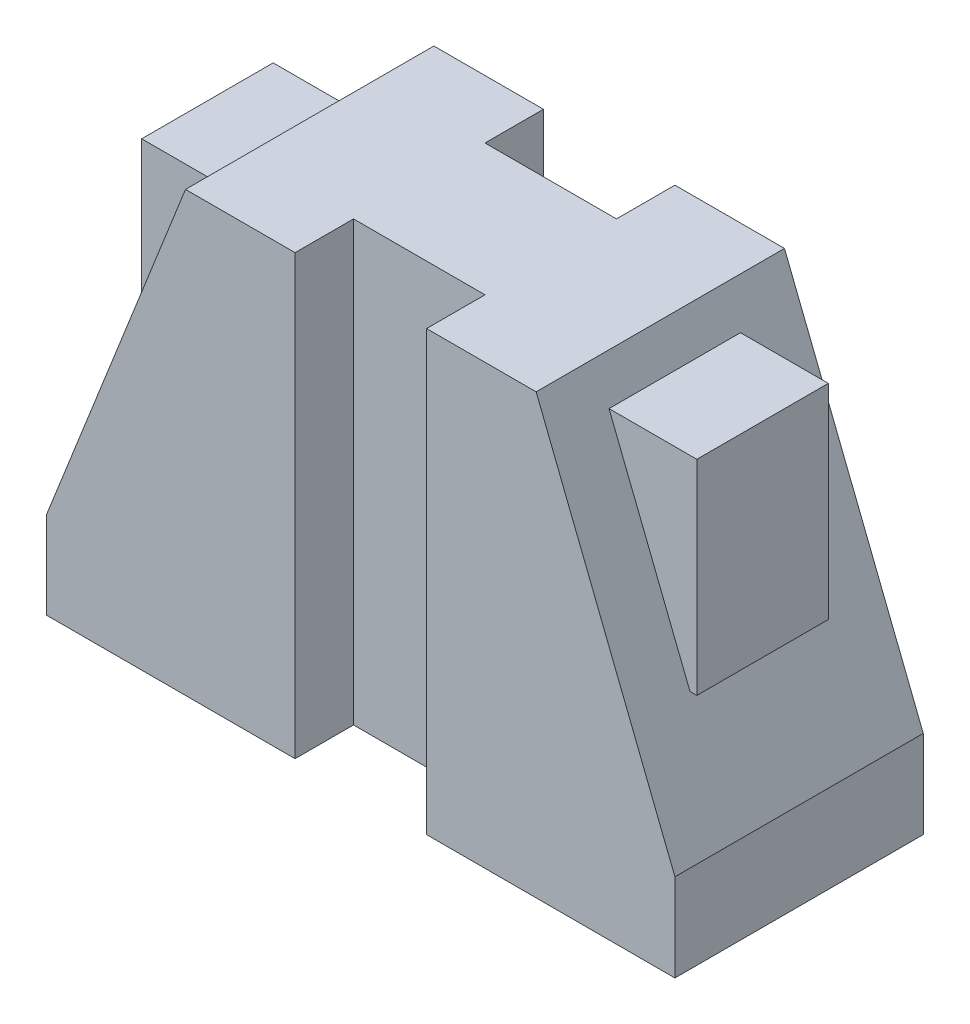
SolidWorks part; units mm, degrees
ref_plane "Front Plane" through (0, 0, 0) normal (0, 0, 1) x (1, 0, 0)
ref_plane "Top Plane" through (0, 0, 0) normal (0, 1, 0) x (1, 0, 0)
ref_plane "Right Plane" through (0, 0, 0) normal (1, 0, 0) x (0, 0, -1)
sketch "Sketch1" plane through (0, 0, 0) normal (0, 0, 1) x (1, 0, 0)
  line L1 (-43, -30) -> (43, -30)
  line L2 (-43, -30) -> (-43, 30)
  line L3 (-43, 30) -> (43, 30)
  line L4 (43, -30) -> (43, 30)
  line L5 (-43, -30) -> (43, 30) construction
  line L6 (-43, 30) -> (43, -30) construction
  point P0 (0, 0)
  dimension "D1" = 86
  dimension "D2" = 60
extrude "Boss-Extrude1" add sketch "Sketch1" along normal mid plane 34
sketch "Sketch2" plane through (0, 0, 0) normal (0, 1, 0) x (1, 0, 0)
  line L0 (43, -17) -> (-43, -17) construction
  line L1 (-9, -9) -> (9, -9)
  line L2 (-9, -9) -> (-9, -17)
  line L3 (-9, -17) -> (9, -17)
  line L4 (9, -9) -> (9, -17)
  line L5 (-9, -9) -> (9, -17) construction
  line L6 (-9, -17) -> (9, -9) construction
  point P0 (0, -13)
  dimension "D1" = 18
  dimension "D2" = 9
extrude "Cut-Extrude1" cut sketch "Sketch2" against normal through all both and the other way through all
mirror "Mirror1" about plane through (0, 0, 0) normal (0, 0, 1) of "Cut-Extrude1"
sketch "Sketch3" plane through (0, 0, 0) normal (0, 0, 1) x (1, 0, 0)
  line L0 (-43, 30) -> (-43, -18)
  line L1 (-43, 30) -> (-43, -30) construction
  line L2 (-43, -18) -> (-24, 30)
  line L3 (-9, 30) -> (-43, 30) construction
  line L4 (-24, 30) -> (-43, 30)
  line L5 (-43, -30) -> (-9, -30) construction
  dimension "D1" = 12
  dimension "D2" = 15
extrude "Cut-Extrude3" cut sketch "Sketch3" against normal through all both and the other way through all
mirror "Mirror2" about plane through (0, 0, 0) normal (1, 0, 0) of "Cut-Extrude3"
sketch "Sketch4" plane through (0, 0, 0) normal (1, 0, 0) x (0, 0, -1)
  line L0 (-17, -18) -> (-17, 30) construction
  line L1 (-9, 25) -> (9, 25)
  line L2 (-9, 25) -> (-9, -3)
  line L3 (-9, -3) -> (9, -3)
  line L4 (9, 25) -> (9, -3)
  line L5 (-9, 25) -> (9, -3) construction
  line L6 (-9, -3) -> (9, 25) construction
  line L7 (17, -18) -> (-17, -18) construction
  point P0 (0, 11)
  point P5 (0, 0)
  dimension "D1" = 28
  dimension "D2" = 8
  dimension "D3" = 15
extrude "Boss-Extrude2" add sketch "Sketch4" along normal mid plane 76
